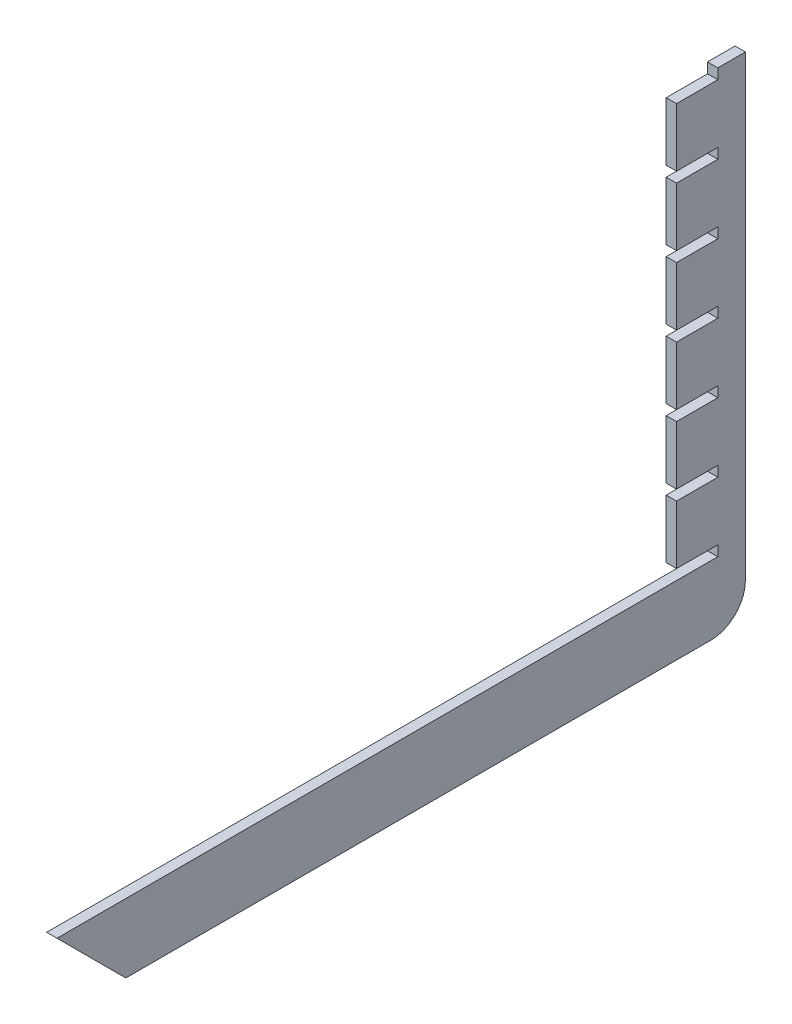
SolidWorks part; units mm, degrees
ref_plane "Front Plane" through (0, 0, 0) normal (0, 0, 1) x (1, 0, 0)
ref_plane "Top Plane" through (0, 0, 0) normal (0, 1, 0) x (1, 0, 0)
ref_plane "Right Plane" through (0, 0, 0) normal (1, 0, 0) x (0, 0, -1)
sketch "Sketch1" plane through (0, 0, 0) normal (1, 0, 0) x (0, 0, -1)
  line L1 (0, 0) -> (20, 0)
  line L2 (0, 0) -> (0, 123)
  line L3 (0, 123) -> (20, 123)
  line L4 (20, 0) -> (20, 123)
  dimension "D1" = 20
  dimension "D2" = 123
extrude "Boss-Extrude1" add sketch "Sketch1" along normal blind 3
sketch "Sketch2" plane through (3, 0, 0) normal (1, 0, 0) x (0, 0, -1)
  line L1 (0, 0) -> (12, 0)
  line L2 (0, 0) -> (0, 3)
  line L3 (0, 3) -> (12, 3)
  line L4 (12, 0) -> (12, 3)
  dimension "D1" = 12
  dimension "D2" = 3
extrude "Cut-Extrude1" cut sketch "Sketch2" against normal through all
pattern_linear "LPattern1" count 7 spacing 20 along (0, 1, 0) of "Cut-Extrude1"
sketch "Sketch3" plane through (0, 0, 0) normal (-1, 0, 0) x (0, 0, 1)
  line L0 (180, 0) -> (160, -20)
  line L1 (-20, 0) -> (180, 0)
  line L2 (-20, 0) -> (-20, -20)
  line L3 (-20, -20) -> (160, -20)
  dimension "D1" = 20
  dimension "D3" = 45
extrude "Boss-Extrude2" add sketch "Sketch3" against normal up to surface (3 mm away) up to face at (3, 61.5, -7.4286)
fillet "Fillet1" radius 10 1 edges at (1.5, -20, -20)
